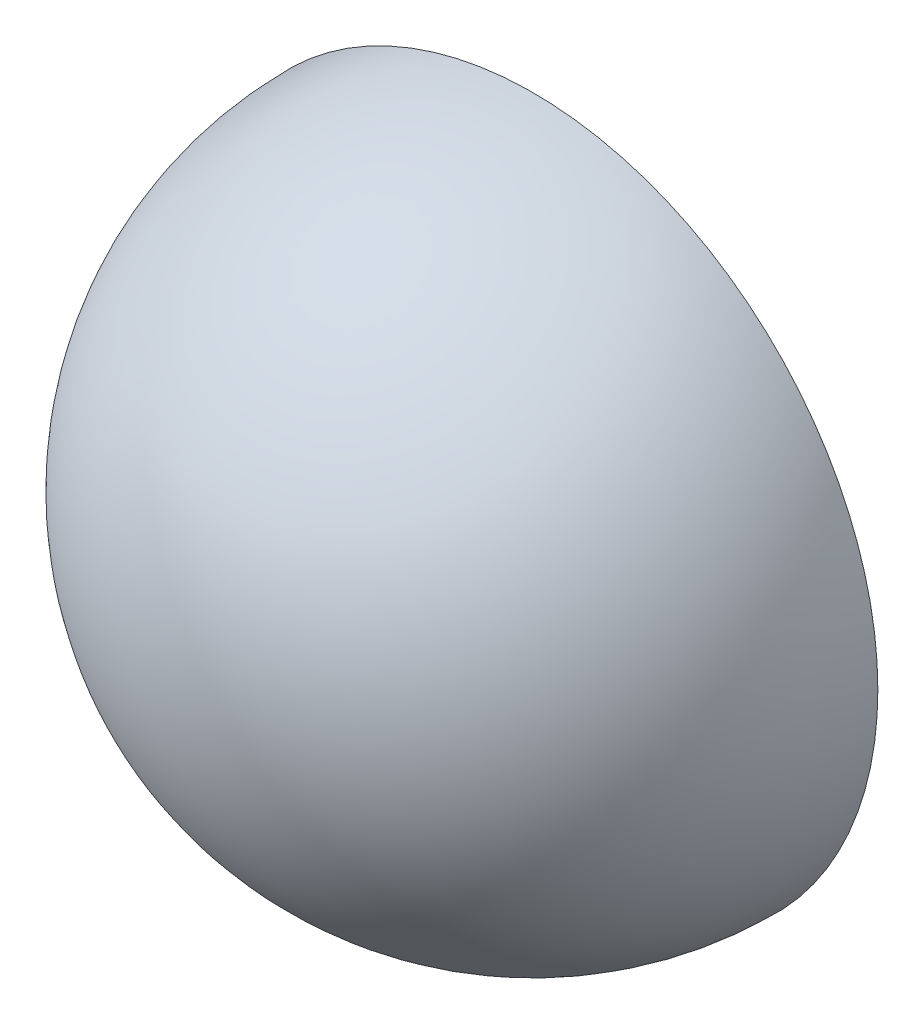
SolidWorks part; units mm, degrees
ref_plane "Front Plane" through (0, 0, 0) normal (0, 0, 1) x (1, 0, 0)
ref_plane "Top Plane" through (0, 0, 0) normal (0, 1, 0) x (1, 0, 0)
ref_plane "Right Plane" through (0, 0, 0) normal (1, 0, 0) x (0, 0, -1)
sketch "Sketch1" plane through (0, 0, 0) normal (0, 0, 1) x (1, 0, 0)
  line L0 (0, 0) -> (0, 60) construction
  line L1 (0, 45) -> (0, 60)
  line L2 (0, 15) -> (0, 0)
  arc A0 (0, 60) -> (0, 0) centre (0, 30) ccw
  arc A1 (0, 45) -> (0, 15) centre (0, 30) ccw
  dimension "D1" = 30
  dimension "D2" = 15
revolve "Revolve1" add sketch "Sketch1" angle 360 about L0
sketch "Sketch2" plane through (0, 0, 0) normal (0, 0, 1) x (1, 0, 0)
  line L1 (-99.1355, 100.28) -> (97.4466, 100.28)
  line L2 (-99.1355, 100.28) -> (-99.1355, -29.4873)
  line L3 (-99.1355, -29.4873) -> (97.4466, -29.4873)
  line L4 (97.4466, 100.28) -> (97.4466, -29.4873)
  line L5 (-99.1355, 100.28) -> (97.4466, -29.4873) construction
  line L6 (-99.1355, -29.4873) -> (97.4466, 100.28) construction
  point P0 (-0.8444, 35.3963)
extrude "Cut-Extrude1" cut sketch "Sketch2" against normal blind 51
